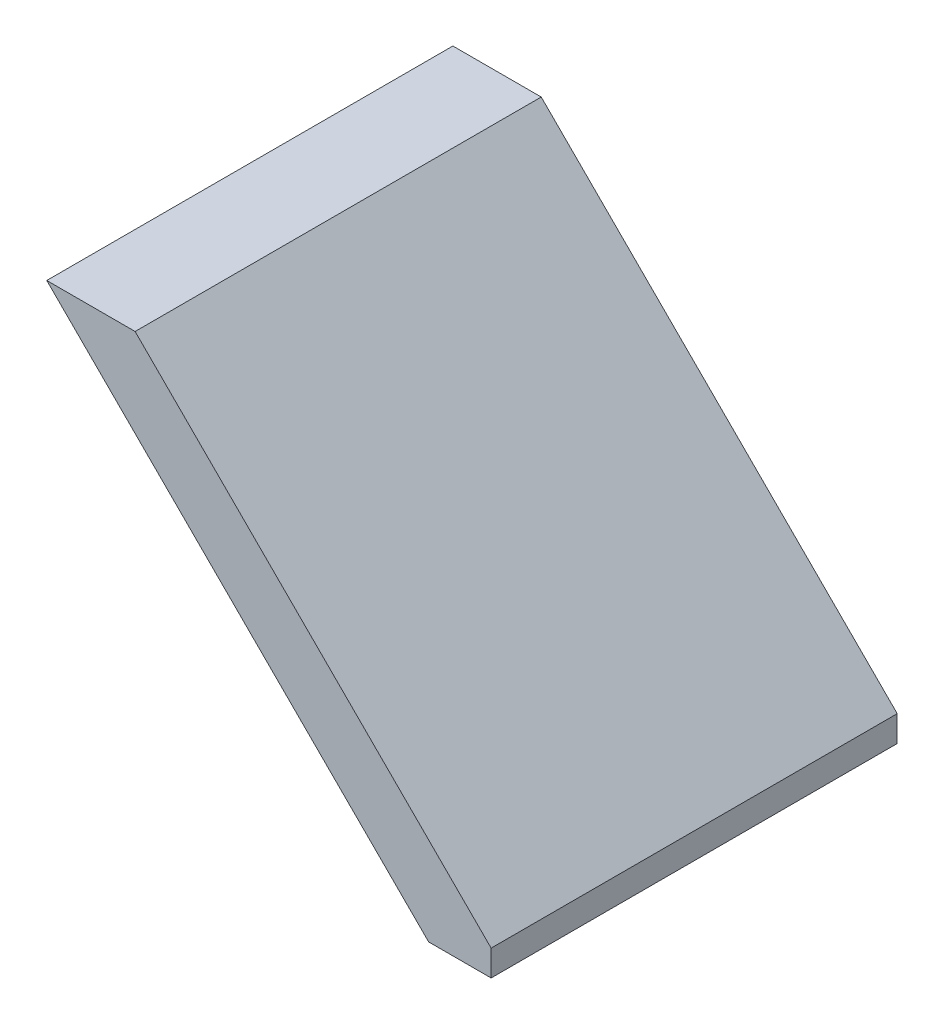
SolidWorks part; units mm, degrees
ref_plane "Front Plane" through (0, 0, 0) normal (0, 0, 1) x (1, 0, 0)
ref_plane "Top Plane" through (0, 0, 0) normal (0, 1, 0) x (1, 0, 0)
ref_plane "Right Plane" through (0, 0, 0) normal (1, 0, 0) x (0, 0, -1)
sketch "Sketch1" plane through (0, 0, 0) normal (0, 0, 1) x (1, 0, 0)
  line L0 (-79, 75) -> (-75, 75)
  line L1 (-79, 75) -> (-75, 75)
  line L2 (-103.45, 99.45) -> (-168.319, 99.45) construction
  line L3 (-79, 75) -> (-103.45, 99.45)
  line L4 (-103.45, 99.45) -> (-97.7931, 99.45)
  line L5 (-192.5, 99.45) -> (-71, 99.45) construction
  line L6 (-97.7931, 99.45) -> (-75, 76.6569)
  line L11 (-75, 40) -> (-75, 99.45) construction
  line L19 (-75, 76.6569) -> (-75, 75)
  dimension "D2" = 45
  dimension "D3" = 4
extrude "Boss-Extrude1" add sketch "Sketch1" against normal up to surface (26 mm away)
